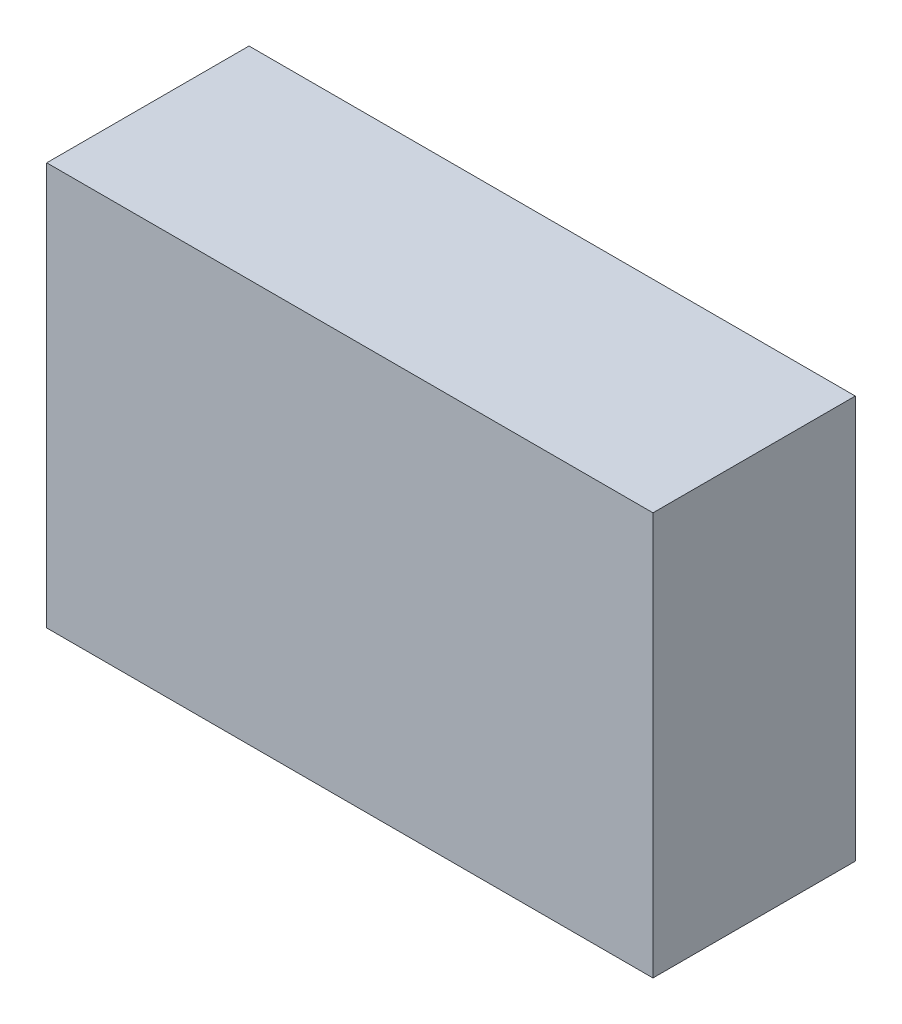
SolidWorks part; units mm, degrees
ref_plane "Ebene vorne" through (0, 0, 0) normal (0, 0, 1) x (1, 0, 0)
ref_plane "Ebene oben" through (0, 0, 0) normal (0, 1, 0) x (1, 0, 0)
ref_plane "Ebene rechts" through (0, 0, 0) normal (1, 0, 0) x (0, 0, -1)
sketch "Skizze1" plane through (0, 0, 0) normal (0, 0, 1) x (1, 0, 0)
  line L0 (-1.4984, 1.0084) -> (1.4984, 1.0084)
  line L1 (1.4984, 1.0084) -> (1.4984, -0.983)
  line L2 (1.4984, -0.983) -> (-1.4984, -0.983)
  line L3 (-1.4984, -0.983) -> (-1.4984, 1.0084)
extrude "Component_Outline" add sketch "Skizze1" along normal blind 1 separate body
sketch3d "3D-Skizze1"
  line L0 (0, 0, 0) -> (1, 0, 0)
  line L1 (0, 0, 0) -> (0, 1, 0)
  line L2 (0, 0, 0) -> (0, 0, 1)
  point P0 (0, 0, 0)
